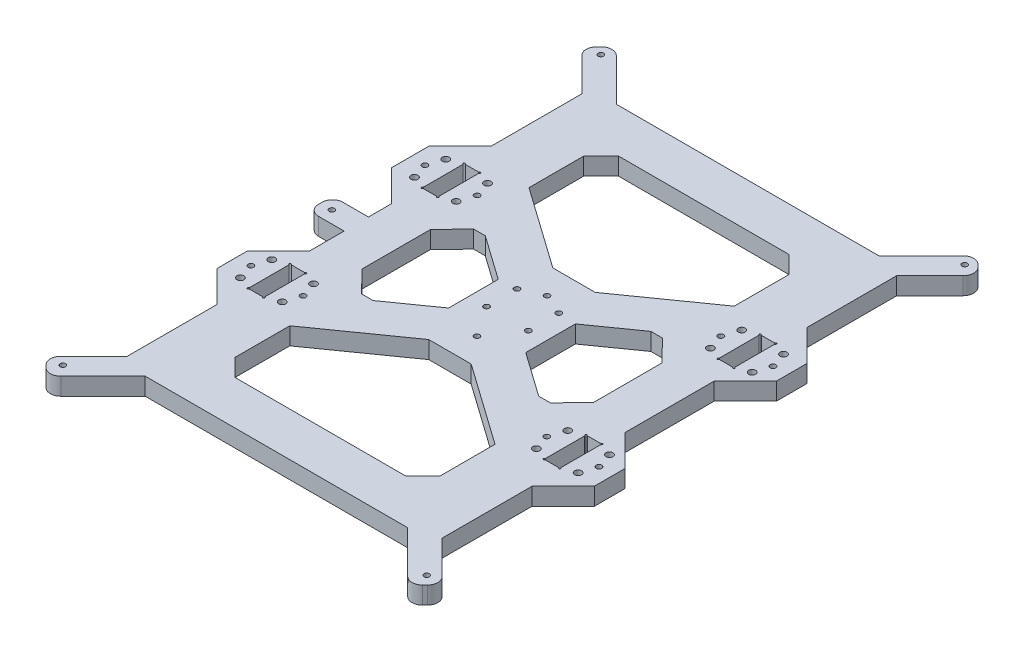
SolidWorks part; units mm, degrees
ref_plane "Alzado" through (0, 0, 0) normal (0, 0, 1) x (1, 0, 0)
ref_plane "Planta" through (0, 0, 0) normal (0, 1, 0) x (1, 0, 0)
ref_plane "Vista lateral" through (0, 0, 0) normal (1, 0, 0) x (0, 0, -1)
sketch "Croquis1" plane through (0, 0, 0) normal (0, 1, 0) x (1, 0, 0)
  line L0 (-39.0365, 19.6293) -> (-39.0365, -19.6293)
  line L2 (-80.7486, 159.562) -> (-82.1628, 158.1478)
  line L3 (-80.9341, 58.992) -> (-80.9341, 60.9895)
  line L4 (-72.2633, 159.562) -> (-47.9941, 135.2928)
  line L5 (-82.1628, 149.6626) -> (-63.0494, 130.5491)
  line L6 (-63.0494, 130.5491) -> (-63.0494, 78.8741)
  line L7 (-63.0494, 78.8741) -> (-72.9315, 68.992)
  line L8 (-63.0494, 21.1259) -> (-63.0494, 7.9985)
  line L9 (-80.9341, -43.5663) -> (-80.9341, -60.9895)
  line L10 (135.7344, 58.992) -> (135.7344, 60.9875)
  line L11 (-31.543, 100.14) -> (-31.543, 68.7002)
  line L12 (-31.543, 100.14) -> (-21.543, 110.14)
  line L13 (-57.6008, -37.9512) -> (-57.6008, -62.0512) construction
  line L14 (135.7344, -43.5683) -> (135.7344, -60.9875)
  line L15 (-61.2348, -37.9512) -> (-53.9668, -37.9512)
  line L16 (-82.1418, -158.1268) -> (-80.7276, -159.541)
  line L17 (-80.9341, 58.992) -> (-80.9341, 39.0105)
  line L18 (135.5366, -159.5516) -> (136.9508, -158.1374)
  line L19 (-77.1008, 155.4985) -> (-77.1008, -153.5015) construction
  line L20 (112.3992, -37.9512) -> (112.3992, -62.0512) construction
  line L21 (108.7652, -37.9512) -> (116.0332, -37.9512)
  line L22 (-72.9315, -35.5638) -> (-80.9341, -43.5663)
  line L23 (-63.0494, 21.1259) -> (-72.9315, 31.008)
  line L24 (117.8478, 130.5491) -> (136.9424, 149.6437)
  line L25 (74.963, 32.2218) -> (49.5544, 14.253)
  line L26 (81.6423, 32.2218) -> (74.963, 32.2218)
  line L27 (-31.543, 68.7002) -> (15.2174, 35.6316)
  line L28 (15.2174, 35.6316) -> (39.581, 35.6316)
  line L29 (93.8349, 19.6293) -> (81.6423, 32.2218)
  line L30 (86.3414, 68.7002) -> (39.581, 35.6316)
  line L31 (-47.9941, 135.2928) -> (102.7925, 135.2928)
  line L32 (117.8478, 25.6817) -> (127.73, 35.5638)
  line L33 (-62.1008, -61.1852) -> (-62.1008, -38.8172)
  line L34 (135.5282, 159.5432) -> (136.9424, 158.129)
  line L35 (107.8992, -61.1852) -> (107.8992, -38.8172)
  line L36 (-39.0365, 19.6293) -> (-26.8439, 32.2218)
  line L37 (-26.8439, 32.2218) -> (-20.1646, 32.2218)
  line L38 (-20.1646, 32.2218) -> (5.244, 14.253)
  line L39 (116.8992, -38.8172) -> (116.8992, -61.1852)
  line L40 (86.3414, 100.14) -> (76.3414, 110.14)
  line L41 (86.3414, 100.14) -> (86.3414, 68.7002)
  line L43 (117.8478, 25.6817) -> (117.8478, -25.6817)
  line L44 (117.8478, 78.8741) -> (127.73, 68.992)
  line L45 (117.8478, 130.5491) -> (117.8478, 78.8741)
  line L46 (127.0429, 159.5432) -> (102.7925, 135.2928)
  line L49 (93.8349, 19.6293) -> (93.8349, -19.6293)
  line L50 (-21.543, 110.14) -> (76.3414, 110.14)
  line L51 (135.7344, 58.992) -> (135.7344, 43.5683)
  line L52 (-63.0494, 0.9985) -> (-77.1008, 0.9985) construction
  line L53 (-63.0494, -6.0015) -> (-77.7317, -6.0015)
  line L54 (-63.0494, -6.0015) -> (-63.0494, -25.6817)
  line L55 (-83.7317, -0.0015) -> (-83.7317, 1.9985)
  line L56 (-63.0494, 7.9985) -> (-77.7317, 7.9985)
  line L57 (112.3992, 62.007) -> (112.3992, 37.907) construction
  line L58 (108.7652, 62.007) -> (116.0332, 62.007)
  line L59 (-72.2423, -159.541) -> (-47.9941, -135.2928)
  line L60 (-21.543, -110.14) -> (76.3414, -110.14)
  line L61 (-63.0494, -130.5491) -> (-82.1418, -149.6415)
  line L62 (102.7925, -135.2928) -> (127.0513, -159.5516)
  line L63 (117.8478, -130.5491) -> (136.9508, -149.6521)
  line L65 (117.8478, -130.5491) -> (117.8478, -78.8741)
  line L66 (117.8478, -78.8741) -> (127.73, -68.992)
  line L67 (86.3414, -100.14) -> (86.3414, -68.7002)
  line L68 (86.3414, -100.14) -> (76.3414, -110.14)
  line L69 (-83.7317, 0.9985) -> (-63.0494, 0.9985) construction
  line L70 (-20.1646, -32.2218) -> (5.244, -14.253)
  line L71 (-26.8439, -32.2218) -> (-20.1646, -32.2218)
  line L72 (-53.1008, -38.8172) -> (-53.1008, -61.1852)
  line L73 (-53.9668, -62.0512) -> (-61.2348, -62.0512)
  line L74 (-39.0365, -19.6293) -> (-26.8439, -32.2218)
  line L75 (122.7992, 57.757) -> (101.9992, 42.157) construction
  line L77 (-53.1008, -46.6262) -> (-62.1008, -53.3762) construction
  line L78 (117.8478, -25.6817) -> (127.73, -35.5638)
  line L79 (-47.9941, -135.2928) -> (102.7925, -135.2928)
  line L80 (86.3414, -68.7002) -> (39.581, -35.6316)
  line L81 (93.8349, -19.6293) -> (81.6423, -32.2218)
  line L82 (15.2174, -35.6316) -> (39.581, -35.6316)
  line L83 (-31.543, -68.7002) -> (15.2174, -35.6316)
  line L84 (81.6423, -32.2218) -> (74.963, -32.2218)
  line L85 (74.963, -32.2218) -> (49.5544, -14.253)
  line L87 (-63.0494, -25.6817) -> (-72.9315, -35.5638)
  line L92 (107.8992, 38.7731) -> (107.8992, 61.141)
  line L93 (116.8992, 61.141) -> (116.8992, 38.7731)
  line L94 (-31.543, -100.14) -> (-21.543, -110.14)
  line L95 (-31.543, -100.14) -> (-31.543, -68.7002)
  line L96 (-63.0494, -78.8741) -> (-72.9315, -68.992)
  line L97 (-63.0494, -130.5491) -> (-63.0494, -78.8741)
  line L267 (27.3992, 135.2928) -> (27.3992, 66.9001) construction
  line L268 (49.5544, 14.253) -> (49.5544, -14.253)
  line L269 (26.7356, 18.7305) -> (34.742, 35.6316) construction
  line L270 (5.244, 14.253) -> (5.244, -14.253)
  line L271 (27.3992, 35.6316) -> (27.3992, 18.5813) construction
  line L272 (27.3992, -18.5813) -> (27.3992, -135.2928) construction
  line L273 (20.0564, 35.6316) -> (28.0628, 18.7305) construction
  line L275 (-72.9315, 68.992) -> (-80.9341, 60.9895)
  line L276 (-61.2348, 62.007) -> (-53.9668, 62.007)
  line L277 (-62.1008, 38.7731) -> (-62.1008, 61.141)
  line L278 (-53.1008, 61.141) -> (-53.1008, 38.7731)
  line L279 (-53.9668, 37.907) -> (-61.2348, 37.907)
  line L280 (-72.9315, -68.992) -> (-80.9341, -60.9895)
  line L281 (127.73, 68.992) -> (135.7344, 60.9875)
  line L282 (116.0332, 37.907) -> (108.7652, 37.907)
  line L284 (-72.9315, 31.008) -> (-80.9341, 39.0105)
  line L285 (116.0332, -62.0512) -> (108.7652, -62.0512)
  line L288 (127.73, 35.5638) -> (135.7344, 43.5683)
  line L289 (127.73, -35.5638) -> (135.7344, -43.5683)
  line L290 (127.73, -68.992) -> (135.7344, -60.9875)
  circle A0 centre (-72.6009, -50.0012) radius 1.6
  arc A1 (-62.1008, -38.8172) -> (-62.3508, -38.3842) centre (-62.6008, -38.8172) ccw
  arc A2 (-61.6678, -37.7012) -> (-62.3508, -38.3842) centre (-62.1008, -37.9512) ccw
  arc A3 (-61.6678, -37.7012) -> (-61.2348, -37.9512) centre (-61.2348, -37.4512) ccw
  circle A4 centre (-72.6009, 49.957) radius 1.6
  circle A5 centre (97.3991, -50.0012) radius 1.6
  circle A6 centre (-77.1008, 155.4985) radius 1.55
  arc A7 (107.8992, -38.8172) -> (107.6492, -38.3842) centre (107.3992, -38.8172) ccw
  circle A8 centre (131.8992, 155.4985) radius 1.55
  arc A9 (108.3322, -37.7012) -> (107.6492, -38.3842) centre (107.8992, -37.9512) ccw
  arc A10 (108.3322, -37.7012) -> (108.7652, -37.9512) centre (108.7652, -37.4512) ccw
  arc A11 (116.0332, -37.9512) -> (116.4662, -37.7012) centre (116.0332, -37.4512) ccw
  arc A12 (117.1492, -38.3842) -> (116.4662, -37.7012) centre (116.8992, -37.9512) ccw
  arc A13 (-62.1008, 61.141) -> (-62.3508, 61.574) centre (-62.6008, 61.141) ccw
  circle A14 centre (97.3991, 49.957) radius 1.6
  circle A15 centre (27.3992, 20.1313) radius 1.55
  arc A16 (107.8992, 61.141) -> (107.6492, 61.574) centre (107.3992, 61.141) ccw
  arc A17 (-53.9668, -37.9512) -> (-53.5338, -37.7012) centre (-53.9668, -37.4512) ccw
  circle A18 centre (27.3992, -20.1313) radius 1.55
  arc A19 (-52.8508, -38.3842) -> (-53.5338, -37.7012) centre (-53.1008, -37.9512) ccw
  circle A20 centre (-77.1008, 0.9985) radius 1.55
  arc A21 (-80.7486, 159.562) -> (-72.2633, 159.562) centre (-76.506, 155.3194) cw
  arc A22 (-82.1628, 158.1478) -> (-82.1628, 149.6626) centre (-77.9202, 153.9052) ccw
  arc A23 (-83.7317, -0.0015) -> (-77.7317, -6.0015) centre (-77.7317, -0.0015) ccw
  circle A24 centre (131.8992, -153.5015) radius 1.55
  arc A25 (-83.7317, 1.9985) -> (-77.7317, 7.9985) centre (-77.7317, 1.9985) cw
  circle A26 centre (-77.1008, -153.5015) radius 1.55
  arc A27 (-80.7276, -159.541) -> (-72.2423, -159.541) centre (-76.4849, -155.2984) ccw
  arc A28 (-61.6678, 62.257) -> (-62.3508, 61.574) centre (-62.1008, 62.007) ccw
  arc A29 (108.3322, 62.257) -> (107.6492, 61.574) centre (107.8992, 62.007) ccw
  arc A30 (-61.6678, 62.257) -> (-61.2348, 62.007) centre (-61.2348, 62.507) ccw
  arc A31 (108.3322, 62.257) -> (108.7652, 62.007) centre (108.7652, 62.507) ccw
  arc A32 (116.0332, 62.007) -> (116.4662, 62.257) centre (116.0332, 62.507) ccw
  arc A33 (117.1492, 61.574) -> (116.4662, 62.257) centre (116.8992, 62.007) ccw
  arc A34 (-82.1418, -158.1268) -> (-82.1418, -149.6415) centre (-77.8992, -153.8842) cw
  arc A35 (135.5366, -159.5516) -> (127.0513, -159.5516) centre (131.2939, -155.3089) cw
  arc A36 (136.9508, -158.1374) -> (136.9508, -149.6521) centre (132.7082, -153.8947) ccw
  arc A37 (136.9424, 158.129) -> (136.9424, 149.6437) centre (132.6998, 153.8864) cw
  arc A38 (127.0429, 159.5432) -> (135.5282, 159.5432) centre (131.2856, 155.3006) cw
  circle A43 centre (100.3992, 58.957) radius 2
  circle A44 centre (124.3992, 58.957) radius 2
  circle A45 centre (124.3992, 40.957) radius 2
  circle A46 centre (100.3992, 40.957) radius 2
  circle A47 centre (100.3992, -41.0012) radius 2
  circle A48 centre (124.3992, -41.0012) radius 2
  circle A49 centre (124.3992, -59.0012) radius 2
  circle A50 centre (100.3992, -59.0012) radius 2
  circle A51 centre (-69.6008, 58.957) radius 2
  circle A52 centre (-45.6008, 58.957) radius 2
  circle A53 centre (-45.6008, 40.957) radius 2
  circle A54 centre (-69.6008, 40.957) radius 2
  circle A55 centre (-69.6008, -41.0012) radius 2
  circle A56 centre (-45.6008, -41.0012) radius 2
  circle A57 centre (-45.6008, -59.0012) radius 2
  circle A58 centre (-69.6008, -59.0012) radius 2
  circle A272 centre (39.3992, 14.8687) radius 1.6
  arc A273 (-53.9668, 62.007) -> (-53.5338, 62.257) centre (-53.9668, 62.507) ccw
  circle A274 centre (15.3992, 14.8687) radius 1.6
  circle A275 centre (39.3992, -2.6313) radius 1.6
  circle A276 centre (15.3992, -2.6313) radius 1.6
  arc A277 (-52.8508, 61.574) -> (-53.5338, 62.257) centre (-53.1008, 62.007) ccw
  arc A278 (-52.8508, 61.574) -> (-53.1008, 61.141) centre (-52.6008, 61.141) ccw
  arc A279 (-53.1008, 38.7731) -> (-52.8508, 38.34) centre (-52.6008, 38.7731) ccw
  arc A280 (-53.5338, 37.657) -> (-52.8508, 38.34) centre (-53.1008, 37.907) ccw
  arc A281 (-53.5338, 37.657) -> (-53.9668, 37.907) centre (-53.9668, 37.407) ccw
  arc A282 (-61.2348, 37.907) -> (-61.6678, 37.657) centre (-61.2348, 37.407) ccw
  arc A283 (-62.3508, 38.3401) -> (-61.6678, 37.657) centre (-62.1008, 37.907) ccw
  arc A284 (-62.3508, 38.3401) -> (-62.1008, 38.7731) centre (-62.6008, 38.7731) ccw
  circle A285 centre (-42.6009, 49.957) radius 1.6
  arc A286 (-52.8508, -38.3842) -> (-53.1008, -38.8172) centre (-52.6008, -38.8172) ccw
  arc A287 (-53.1008, -61.1852) -> (-52.8508, -61.6182) centre (-52.6008, -61.1852) ccw
  arc A288 (-53.5338, -62.3012) -> (-52.8508, -61.6182) centre (-53.1008, -62.0512) ccw
  arc A289 (-53.5338, -62.3012) -> (-53.9668, -62.0512) centre (-53.9668, -62.5512) ccw
  arc A290 (-61.2348, -62.0512) -> (-61.6678, -62.3012) centre (-61.2348, -62.5512) ccw
  arc A291 (-62.3508, -61.6182) -> (-61.6678, -62.3012) centre (-62.1008, -62.0512) ccw
  arc A292 (-62.3508, -61.6182) -> (-62.1008, -61.1852) centre (-62.6008, -61.1852) ccw
  circle A293 centre (-42.6009, -50.0012) radius 1.6
  arc A294 (117.1492, 61.574) -> (116.8992, 61.141) centre (117.3992, 61.141) ccw
  arc A295 (116.8992, 38.7731) -> (117.1492, 38.34) centre (117.3992, 38.7731) ccw
  arc A296 (116.4662, 37.657) -> (117.1492, 38.34) centre (116.8992, 37.907) ccw
  arc A297 (116.4662, 37.657) -> (116.0332, 37.907) centre (116.0332, 37.407) ccw
  arc A298 (108.7652, 37.907) -> (108.3322, 37.657) centre (108.7652, 37.407) ccw
  arc A299 (107.6492, 38.3401) -> (108.3322, 37.657) centre (107.8992, 37.907) ccw
  arc A300 (107.6492, 38.3401) -> (107.8992, 38.7731) centre (107.3992, 38.7731) ccw
  circle A301 centre (127.3991, 49.957) radius 1.6
  arc A302 (117.1492, -38.3842) -> (116.8992, -38.8172) centre (117.3992, -38.8172) ccw
  arc A303 (116.8992, -61.1852) -> (117.1492, -61.6182) centre (117.3992, -61.1852) ccw
  arc A304 (116.4662, -62.3012) -> (117.1492, -61.6182) centre (116.8992, -62.0512) ccw
  arc A305 (116.4662, -62.3012) -> (116.0332, -62.0512) centre (116.0332, -62.5512) ccw
  arc A306 (108.7652, -62.0512) -> (108.3322, -62.3012) centre (108.7652, -62.5512) ccw
  arc A307 (107.6492, -61.6182) -> (108.3322, -62.3012) centre (107.8992, -62.0512) ccw
  arc A308 (107.6492, -61.6182) -> (107.8992, -61.1852) centre (107.3992, -61.1852) ccw
  circle A309 centre (127.3991, -50.0012) radius 1.6
  point P1 (-31.543, -110.14)
  point P8 (-63.0494, 0.9985)
  point P62 (-39.0365, 0)
  point P65 (27.3992, 110.14)
  point P73 (27.3992, 135.2928)
  point P74 (27.3992, 35.6316)
  point P89 (86.3414, 110.14)
  point P127 (-31.543, 110.14)
  point P135 (-57.6008, 49.957)
  point P160 (93.8349, 0)
  point P167 (117.8478, 0)
  point P189 (-39.0365, 0)
  point P193 (86.3414, -110.14)
  point P194 (27.3992, -35.6316)
  point P195 (27.3992, -135.2928)
  point P196 (27.3992, -110.14)
  dimension "D1" = 309
  dimension "D8" = 3.1
  dimension "D2" = 309
  dimension "D3" = 209
  dimension "D4" = 154.5
  dimension "D7" = 6
  dimension "D9" = 6
  dimension "D10" = 6
  dimension "D11" = 6
  dimension "D12" = 6
  dimension "D5" = 14
  dimension "D6" = 154.5
extrude "Saliente-Extruir1" add sketch "Croquis1" along normal blind 10
